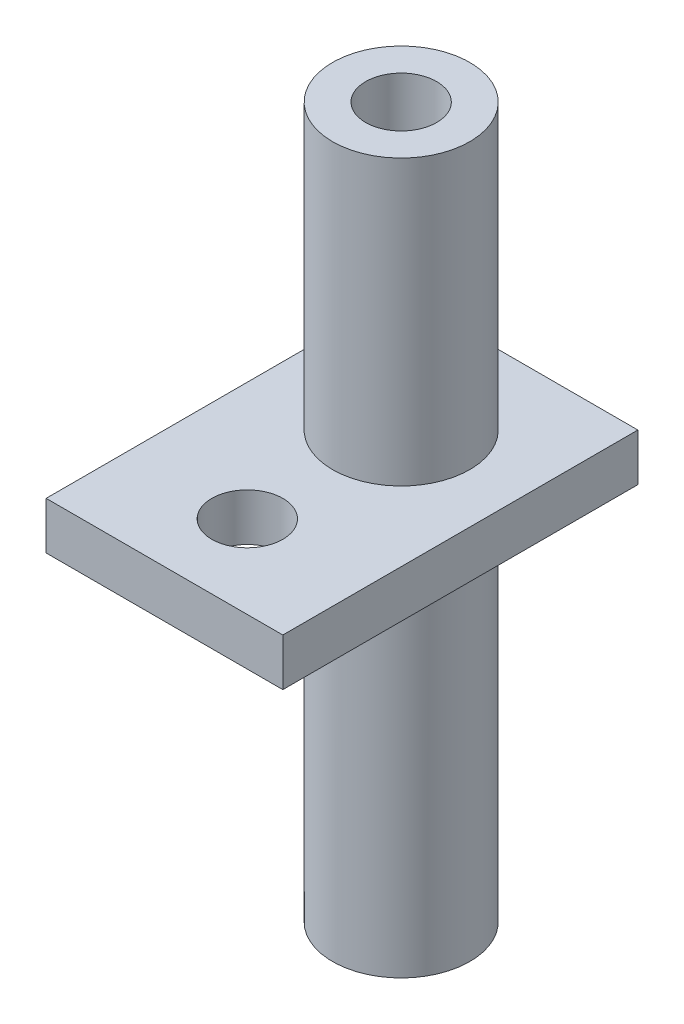
SolidWorks part; units mm, degrees
ref_plane "前视基准面" through (0, 0, 0) normal (0, 0, 1) x (1, 0, 0)
ref_plane "上视基准面" through (0, 0, 0) normal (0, 1, 0) x (1, 0, 0)
ref_plane "右视基准面" through (0, 0, 0) normal (1, 0, 0) x (0, 0, -1)
other "Configuration Table"
sketch "草图1" plane through (0, 0, 0) normal (0, 1, 0) x (1, 0, 0)
  circle A0 centre (0, 0) radius 2.9
  circle A1 centre (0, 0) radius 1.5
  dimension "D1" = 5.8
  dimension "D2" = 3
extrude "凸台-拉伸1" add sketch "草图1" along normal blind 40
ref_plane "基准面1" through (0, 28, 0) normal (0, 1, 0) x (1, 0, 0)
sketch "草图2" plane through (0, 28, 0) normal (0, 1, 0) x (1, 0, 0)
  line L0 (0, 0) -> (0, 5)
  line L1 (0, 5) -> (-5, 5)
  line L3 (-5, 5) -> (5, 5)
  line L4 (-5, 5) -> (-5, -10)
  line L5 (-5, -10) -> (5, -10)
  line L6 (5, 5) -> (5, -10)
  circle A0 centre (0, -6.5) radius 1.5
  dimension "D1" = 3
  dimension "D2" = 6.5
  dimension "D3" = 5
  dimension "D4" = 5
  dimension "D5" = 10
  dimension "D6" = 15
extrude "凸台-拉伸2" add sketch "草图2" against normal blind 2
ref_plane "基准面2" through (0, 10, 0) normal (0, -1, 0) x (-1, 0, 0)
sketch "草图3" plane through (0, 10, 0) normal (0, -1, 0) x (-1, 0, 0)
  circle A0 centre (0, 0) radius 2.9
extrude "切除-拉伸1" cut sketch "草图3" along normal through all
